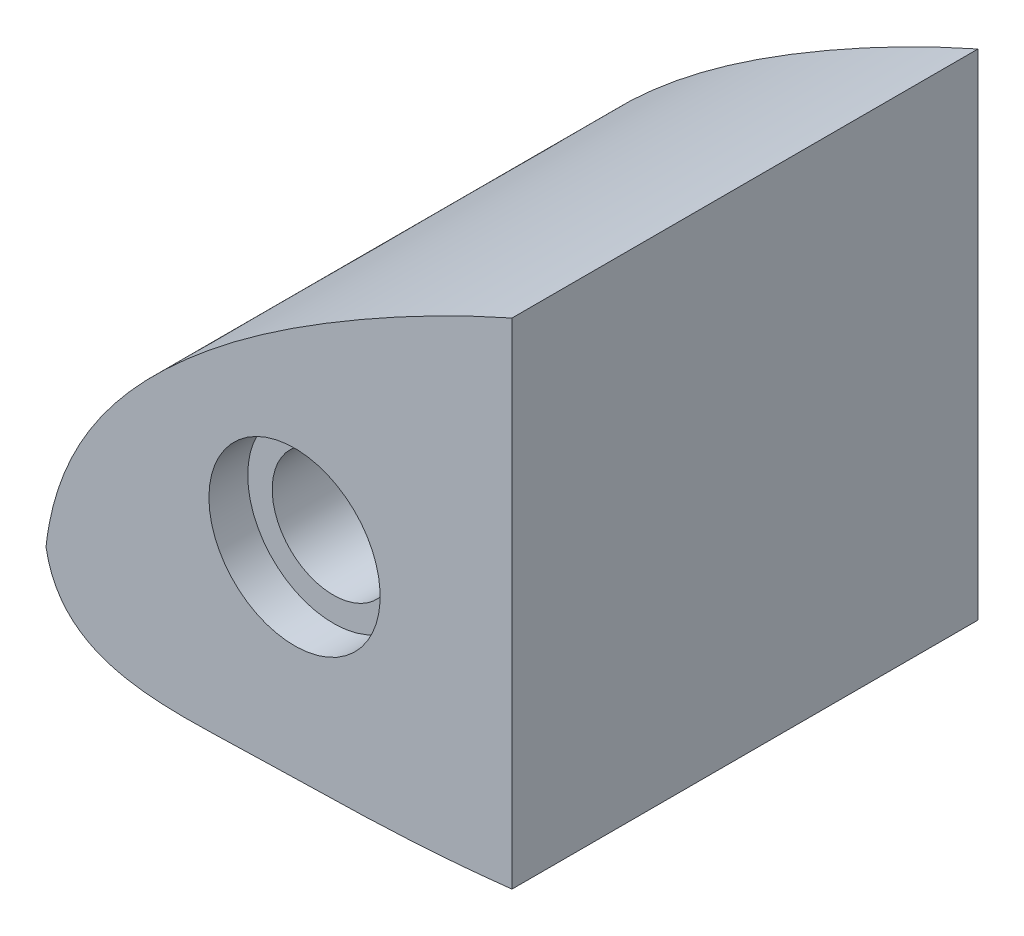
SolidWorks part; units mm, degrees
ref_plane "Front Plane" through (0, 0, 0) normal (0, 0, 1) x (1, 0, 0)
ref_plane "Top Plane" through (0, 0, 0) normal (0, 1, 0) x (1, 0, 0)
ref_plane "Right Plane" through (0, 0, 0) normal (1, 0, 0) x (0, 0, -1)
sketch "Sketch1" plane through (0, 0, 0) normal (0, 0, 1) x (1, 0, 0)
  spline S0 degree 3 poles (0.0006, 0.0001) (0.8106, 7.3592) (8.6491, 17.8566) (26.2867, 29.9752) (52.1111, 42.0692) (89.5976, 49.2908) (131.4008, 47.8848) (173.2567, 40.0411) (217.9611, 29.613) (256.9521, 19.5289) (290.3598, 8.711) (301.2732, 4.3828) (314.8169, -0.5162) (309.8463, 0.0001) knots 0 0 0 0 0.060864 0.113688 0.188609 0.312909 0.448482 0.557612 0.691544 0.852438 0.929756 0.976058 1 1 1 1
  spline S1 degree 3 poles (309.8463, 0.0001) (303.9568, 1.471) (293.9895, 2.094) (276.264, 4.5144) (260.8463, 5.4274) (235.8588, 7.8703) (205.1014, 8.8381) (157.7186, 9.0307) (110.4973, 6.1815) (66.5062, -0.5867) (36.4547, -6.0985) (15.3166, -6.1891) (1.2307, -6.9241) (0.0006, 0.0001) knots 0 0 0 0 0.057787 0.095275 0.171021 0.205339 0.335319 0.464904 0.658702 0.785512 0.893517 0.943092 1 1 1 1
extrude "Boss-Extrude1" add sketch "Sketch1" along normal blind 38.1
sketch "Sketch2" plane through (0, 0, 38.1) normal (0, 0, 1) x (1, 0, 0)
  circle A0 centre (20.32, 10.16) radius 5
  circle A1 centre (227.2963, 19.0501) radius 3.175
  dimension "D2" = 10
  dimension "D3" = 6.35
  dimension "D6" = 20.32
  dimension "D1" = 82.55
  dimension "D4" = 19.05
  dimension "D5" = 10.16
extrude "Cut-Extrude1" cut sketch "Sketch2" against normal through all
sketch "Sketch3" plane through (0, 0, 38.1) normal (0, 0, 1) x (1, 0, 0)
  line L1 (38.1, 71.718) -> (331.2889, 71.718)
  line L2 (38.1, 71.718) -> (38.1, -66.2532)
  line L3 (38.1, -66.2532) -> (331.2889, -66.2532)
  line L4 (331.2889, 71.718) -> (331.2889, -66.2532)
  dimension "D1" = 38.1
extrude "Cut-Extrude2" cut sketch "Sketch3" against normal through all
sketch "Sketch4" plane through (0, 0, 0) normal (0, 0, -1) x (-1, 0, 0)
  circle A0 centre (-20.32, 10.16) radius 7
  dimension "D1" = 14
extrude "Cut-Extrude3" cut sketch "Sketch4" along normal blind 3.175 from surface at -38.1 starting at face at (25.32, 10.16, 38.1)
